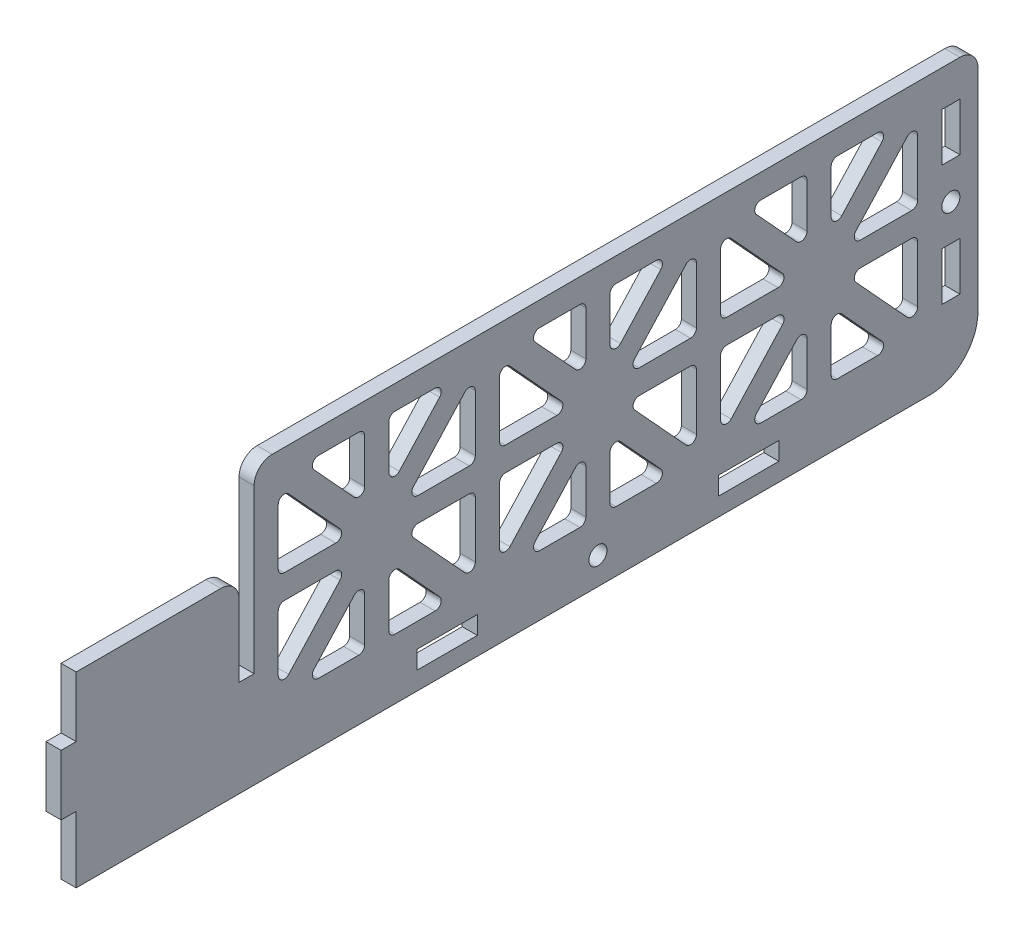
SolidWorks part; units mm, degrees
ref_plane "前视基准面" through (0, 0, 0) normal (0, 0, 1) x (1, 0, 0)
ref_plane "上视基准面" through (0, 0, 0) normal (0, 1, 0) x (1, 0, 0)
ref_plane "右视基准面" through (0, 0, 0) normal (1, 0, 0) x (0, 0, -1)
sketch "草图1" plane through (0, 0, 0) normal (1, 0, 0) x (0, 0, -1)
  line L0 (13.5, 31) -> (13.5, 21.3808) construction
  line L1 (0, 0) -> (149.5, 0)
  line L8 (0, 31) -> (0, 21)
  line L9 (29.5, 16) -> (27, 16)
  line L10 (27, 31) -> (27, 16)
  line L12 (29.5, 46) -> (29.5, 16)
  line L13 (0, 31) -> (27, 31)
  line L16 (0, 0) -> (0, 11)
  line L17 (0, 11) -> (-2.5, 11)
  line L18 (-2.5, 11) -> (-2.5, 21)
  line L19 (-2.5, 21) -> (0, 21)
  line L20 (-2.5, 16) -> (0, 16) construction
  line L21 (29.5, 46) -> (149.5, 46)
  line L22 (149.5, 46) -> (149.5, 0)
  line L23 (130, 26) -> (114.5458, 26) construction
  line L31 (143.5, 40) -> (146.5, 40)
  line L32 (143.5, 40) -> (143.5, 32)
  line L33 (143.5, 32) -> (146.5, 32)
  line L34 (146.5, 40) -> (146.5, 32)
  line L36 (29.5, 16) -> (29.5, 0) construction
  line L37 (29.5, 6) -> (149.5, 6) construction
  line L38 (29.5, 3) -> (149.5, 3) construction
  line L39 (143.5, 20) -> (146.5, 20)
  line L40 (146.5, 12) -> (146.5, 20)
  line L41 (143.5, 12) -> (146.5, 12)
  line L42 (143.5, 12) -> (143.5, 20)
  line L43 (86.5, 6) -> (86.5, 3) construction
  line L44 (116.5, 3) -> (106.5, 3)
  line L45 (56.5, 6) -> (66.5, 6)
  line L46 (56.5, 6) -> (56.5, 3)
  line L47 (56.5, 3) -> (66.5, 3)
  line L48 (66.5, 6) -> (66.5, 3)
  line L49 (106.5, 6) -> (106.5, 3)
  line L50 (116.5, 6) -> (106.5, 6)
  line L51 (116.5, 6) -> (116.5, 3)
  line L52 (145, 32) -> (145, 26) construction
  line L53 (143.5, 20) -> (143.5, 0) construction
  circle A0 centre (86.5, 4.5) radius 1.5
  circle A1 centre (145, 26) radius 1.5
  point P16 (124.3084, 26)
  point P43 (106.5, 4.5)
  point P50 (89.5, 8.9549)
  point P51 (85.2816, 6.0159)
  point P52 (0, 0)
  point P53 (86.5, 6)
  point P54 (86.5, 3.9937)
  dimension "D18" = 3
  dimension "D1" = 31
  dimension "D2" = 2.5
  dimension "D3" = 27
  dimension "D4" = 2.5
  dimension "D5" = 10
  dimension "D6" = 30
  dimension "D7" = 120
  dimension "D8" = 12
  dimension "D9" = 15
  dimension "D10" = 15
  dimension "D11" = 3
  dimension "D12" = 8
  dimension "D13" = 3
  dimension "D14" = 3
  dimension "D15" = 3
  dimension "D16" = 10
  dimension "D17" = 40
extrude "凸台-拉伸1" add sketch "草图1" along normal blind 2.5 contours L8 L19 L18 L17 L16 L1 L22 L21 L12 L9 L10 L13
fillet "圆角1" radius 8 1 edges at (1.25, 0, -149.5)
fillet "圆角2" radius 3 3 edges at (1.25, 31, -27) (1.25, 46, -29.5) (1.25, 46, -149.5)
sketch "草图2" plane through (2.5, 0, 0) normal (1, 0, 0) x (0, 0, -1)
  line L0 (31.5, 6) -> (141.5, 6) construction
  line L1 (19.094, 109.9766) -> (51.3293, 109.9766) construction
  line L2 (19.094, 109.9766) -> (19.094, 72.6515) construction
  line L3 (19.094, 72.6515) -> (51.3293, 72.6515) construction
  line L4 (51.3293, 109.9766) -> (51.3293, 72.6515) construction
  line L5 (19.094, 109.9766) -> (51.3293, 72.6515) construction
  line L6 (19.094, 72.6515) -> (51.3293, 109.9766) construction
  line L7 (141.5, 6) -> (141.5, 41) construction
  line L8 (141.5, 41) -> (31.5, 41) construction
  line L9 (31.5, 41) -> (31.5, 6) construction
  line L10 (29.5, 43) -> (29.5, 16) construction
  line L11 (146.5, 46) -> (32.5, 46) construction
  line L12 (143.5, 40) -> (143.5, 32) construction
  line L13 (68.1667, 41) -> (68.1667, 6) construction
  line L14 (35.2116, 109.9766) -> (35.2116, 72.6515) construction
  line L15 (19.094, 91.314) -> (51.3293, 91.314) construction
  line L16 (21.094, 104.6009) -> (21.094, 93.0145)
  line L17 (21.094, 93.0145) -> (31.1005, 93.0145)
  line L18 (31.1005, 93.0145) -> (21.094, 104.6009)
  line L19 (25.1911, 105.9766) -> (33.2116, 96.6897)
  line L20 (33.2116, 96.6897) -> (33.2116, 105.9766)
  line L21 (33.2116, 105.9766) -> (25.1911, 105.9766)
  line L22 (37.2116, 105.9766) -> (45.2321, 105.9766)
  line L23 (37.2116, 96.6897) -> (37.2116, 105.9766)
  line L24 (45.2321, 105.9766) -> (37.2116, 96.6897)
  line L25 (49.3293, 93.0145) -> (39.3228, 93.0145)
  line L26 (49.3293, 104.6009) -> (49.3293, 93.0145)
  line L27 (39.3228, 93.0145) -> (49.3293, 104.6009)
  line L28 (49.3293, 78.0271) -> (49.3293, 89.6136)
  line L29 (39.3228, 89.6136) -> (49.3293, 78.0271)
  line L30 (49.3293, 89.6136) -> (39.3228, 89.6136)
  line L31 (37.2116, 85.9384) -> (37.2116, 76.6515)
  line L32 (45.2321, 76.6515) -> (37.2116, 85.9384)
  line L33 (37.2116, 76.6515) -> (45.2321, 76.6515)
  line L34 (33.2116, 76.6515) -> (25.1911, 76.6515)
  line L35 (33.2116, 85.9384) -> (33.2116, 76.6515)
  line L36 (25.1911, 76.6515) -> (33.2116, 85.9384)
  line L37 (21.094, 89.6136) -> (31.1005, 89.6136)
  line L38 (21.094, 78.0271) -> (21.094, 89.6136)
  line L39 (31.1005, 89.6136) -> (21.094, 78.0271)
  line L40 (31.5, 46) -> (68.1667, 46) construction
  line L41 (31.5, 46) -> (31.5, 6) construction
  line L42 (31.5, 6) -> (68.1667, 6) construction
  line L43 (68.1667, 46) -> (68.1667, 6) construction
  line L44 (31.5, 46) -> (68.1667, 6) construction
  line L45 (31.5, 6) -> (68.1667, 46) construction
  line L46 (49.8333, 46) -> (49.8333, 6) construction
  line L47 (31.5, 26) -> (68.1667, 26) construction
  line L48 (33.5, 40.8584) -> (33.5, 28)
  line L49 (33.5, 28) -> (45.2869, 28)
  line L50 (45.2869, 28) -> (33.5, 40.8584)
  line L51 (37.8798, 42) -> (47.8333, 31.1416)
  line L52 (47.8333, 31.1416) -> (47.8333, 42)
  line L53 (47.8333, 42) -> (37.8798, 42)
  line L54 (51.8333, 42) -> (61.7869, 42)
  line L55 (51.8333, 31.1416) -> (51.8333, 42)
  line L56 (61.7869, 42) -> (51.8333, 31.1416)
  line L57 (66.1667, 28) -> (54.3798, 28)
  line L58 (66.1667, 40.8584) -> (66.1667, 28)
  line L59 (54.3798, 28) -> (66.1667, 40.8584)
  line L60 (66.1667, 11.1416) -> (66.1667, 24)
  line L61 (54.3798, 24) -> (66.1667, 11.1416)
  line L62 (66.1667, 24) -> (54.3798, 24)
  line L63 (51.8333, 20.8584) -> (51.8333, 10)
  line L64 (61.7869, 10) -> (51.8333, 20.8584)
  line L65 (51.8333, 10) -> (61.7869, 10)
  line L66 (47.8333, 10) -> (37.8798, 10)
  line L67 (47.8333, 20.8584) -> (47.8333, 10)
  line L68 (37.8798, 10) -> (47.8333, 20.8584)
  line L69 (33.5, 24) -> (45.2869, 24)
  line L70 (33.5, 11.1416) -> (33.5, 24)
  line L71 (45.2869, 24) -> (33.5, 11.1416)
  line L72 (66.5, 6) -> (56.5, 6) construction
  line L73 (68.1667, 46) -> (104.8333, 46) construction
  line L74 (68.1667, 46) -> (68.1667, 6) construction
  line L75 (68.1667, 6) -> (104.8333, 6) construction
  line L76 (104.8333, 46) -> (104.8333, 6) construction
  line L77 (68.1667, 46) -> (104.8333, 6) construction
  line L78 (68.1667, 6) -> (104.8333, 46) construction
  line L79 (86.5, 46) -> (86.5, 6) construction
  line L80 (68.1667, 26) -> (104.8333, 26) construction
  line L81 (70.1667, 40.8584) -> (70.1667, 28)
  line L82 (70.1667, 28) -> (81.9535, 28)
  line L83 (81.9535, 28) -> (70.1667, 40.8584)
  line L84 (74.5465, 42) -> (84.5, 31.1416)
  line L85 (84.5, 31.1416) -> (84.5, 42)
  line L86 (84.5, 42) -> (74.5465, 42)
  line L87 (88.5, 42) -> (98.4535, 42)
  line L88 (88.5, 31.1416) -> (88.5, 42)
  line L89 (98.4535, 42) -> (88.5, 31.1416)
  line L90 (102.8333, 28) -> (91.0465, 28)
  line L91 (102.8333, 40.8584) -> (102.8333, 28)
  line L92 (91.0465, 28) -> (102.8333, 40.8584)
  line L93 (102.8333, 11.1416) -> (102.8333, 24)
  line L94 (91.0465, 24) -> (102.8333, 11.1416)
  line L95 (102.8333, 24) -> (91.0465, 24)
  line L96 (88.5, 20.8584) -> (88.5, 10)
  line L97 (98.4535, 10) -> (88.5, 20.8584)
  line L98 (88.5, 10) -> (98.4535, 10)
  line L99 (84.5, 10) -> (74.5465, 10)
  line L100 (84.5, 20.8584) -> (84.5, 10)
  line L101 (74.5465, 10) -> (84.5, 20.8584)
  line L102 (70.1667, 24) -> (81.9535, 24)
  line L103 (70.1667, 11.1416) -> (70.1667, 24)
  line L104 (81.9535, 24) -> (70.1667, 11.1416)
  line L105 (104.8333, 59.7367) -> (104.8333, 24.7367) construction
  line L106 (104.8333, 46) -> (141.5, 46) construction
  line L107 (104.8333, 46) -> (104.8333, 6) construction
  line L108 (104.8333, 6) -> (141.5, 6) construction
  line L109 (141.5, 46) -> (141.5, 6) construction
  line L110 (104.8333, 46) -> (141.5, 6) construction
  line L111 (104.8333, 6) -> (141.5, 46) construction
  line L112 (123.1667, 46) -> (123.1667, 6) construction
  line L113 (104.8333, 26) -> (141.5, 26) construction
  line L114 (106.8333, 40.8584) -> (106.8333, 28)
  line L115 (106.8333, 28) -> (118.6202, 28)
  line L116 (118.6202, 28) -> (106.8333, 40.8584)
  line L117 (111.2131, 42) -> (121.1667, 31.1416)
  line L118 (121.1667, 31.1416) -> (121.1667, 42)
  line L119 (121.1667, 42) -> (111.2131, 42)
  line L120 (125.1667, 42) -> (135.1202, 42)
  line L121 (125.1667, 31.1416) -> (125.1667, 42)
  line L122 (135.1202, 42) -> (125.1667, 31.1416)
  line L123 (139.5, 28) -> (127.7131, 28)
  line L124 (139.5, 40.8584) -> (139.5, 28)
  line L125 (127.7131, 28) -> (139.5, 40.8584)
  line L126 (139.5, 11.1416) -> (139.5, 24)
  line L127 (127.7131, 24) -> (139.5, 11.1416)
  line L128 (139.5, 24) -> (127.7131, 24)
  line L129 (125.1667, 20.8584) -> (125.1667, 10)
  line L130 (135.1202, 10) -> (125.1667, 20.8584)
  line L131 (125.1667, 10) -> (135.1202, 10)
  line L132 (121.1667, 10) -> (111.2131, 10)
  line L133 (121.1667, 20.8584) -> (121.1667, 10)
  line L134 (111.2131, 10) -> (121.1667, 20.8584)
  line L135 (106.8333, 24) -> (118.6202, 24)
  line L136 (106.8333, 11.1416) -> (106.8333, 24)
  line L137 (118.6202, 24) -> (106.8333, 11.1416)
  point P0 (35.2116, 91.314)
  point P24 (0, 0)
  point P28 (23.4317, 107.5992)
  point P47 (49.8333, 26)
  point P82 (86.5, 26)
  point P117 (123.1667, 26)
  dimension "D1" = 2
  dimension "D2" = 5
  dimension "D3" = 2
  dimension "D4" = 4
  dimension "D5" = 4
  dimension "D6" = 4
  dimension "D7" = 4
  dimension "D8" = 2
  dimension "D9" = 4
  dimension "D10" = 4
  dimension "D11" = 4
  dimension "D12" = 2
  dimension "D13" = 4
  dimension "D14" = 4
  dimension "D15" = 4
  dimension "D16" = 2
  dimension "D17" = 4
  dimension "D18" = 4
  dimension "D19" = 4
  dimension "D20" = 4
  dimension "D21" = 2
  dimension "D22" = 4
extrude "切除-拉伸1" cut sketch "草图2" against normal through all
fillet "圆角3" radius 1 72 edges at (1.25, 10, -88.5) (1.25, 20.8584, -88.5) (1.25, 10, -98.4535) (1.25, 10, -74.5465) (1.25, 20.8584, -84.5) (1.25, 10, -84.5) (1.25, 24, -81.9535) (1.25, 11.1416, -70.1667) (1.25, 24, -70.1667) (1.25, 28, -106.8333) (1.25, 40.8584, -106.8333) (1.25, 28, -118.6202) (1.25, 42, -74.5465) (1.25, 42, -84.5) (1.25, 31.1416, -84.5) (1.25, 42, -98.4535) (1.25, 31.1416, -88.5) (1.25, 42, -88.5) (1.25, 28, -91.0465) (1.25, 40.8584, -102.8333) (1.25, 28, -102.8333) (1.25, 24, -102.8333) (1.25, 11.1416, -102.8333) (1.25, 24, -91.0465) (1.25, 10, -125.1667) (1.25, 20.8584, -125.1667) (1.25, 10, -135.1202) (1.25, 10, -111.2131) (1.25, 20.8584, -121.1667) (1.25, 10, -121.1667) (1.25, 24, -118.6202) (1.25, 11.1416, -106.8333) (1.25, 24, -106.8333) (1.25, 42, -111.2131) (1.25, 42, -121.1667) (1.25, 31.1416, -121.1667) (1.25, 42, -135.1202) (1.25, 31.1416, -125.1667) (1.25, 42, -125.1667) (1.25, 28, -127.7131) (1.25, 40.8584, -139.5) (1.25, 28, -139.5) (1.25, 24, -139.5) (1.25, 11.1416, -139.5) (1.25, 24, -127.7131) (1.25, 28, -33.5) (1.25, 28, -45.2869) (1.25, 10, -51.8333) (1.25, 20.8584, -51.8333) (1.25, 10, -61.7869) (1.25, 10, -37.8798) (1.25, 20.8584, -47.8333) (1.25, 10, -47.8333) (1.25, 24, -45.2869) (1.25, 11.1416, -33.5) (1.25, 24, -33.5) (1.25, 28, -70.1667) (1.25, 40.8584, -70.1667) (1.25, 28, -81.9535) (1.25, 42, -37.8798) (1.25, 42, -47.8333) (1.25, 31.1416, -47.8333) (1.25, 42, -61.7869) (1.25, 31.1416, -51.8333) (1.25, 42, -51.8333) (1.25, 28, -54.3798) (1.25, 40.8584, -66.1667) (1.25, 28, -66.1667) (1.25, 24, -66.1667) (1.25, 11.1416, -66.1667) (1.25, 24, -54.3798) (1.25, 40.8584, -33.5)
